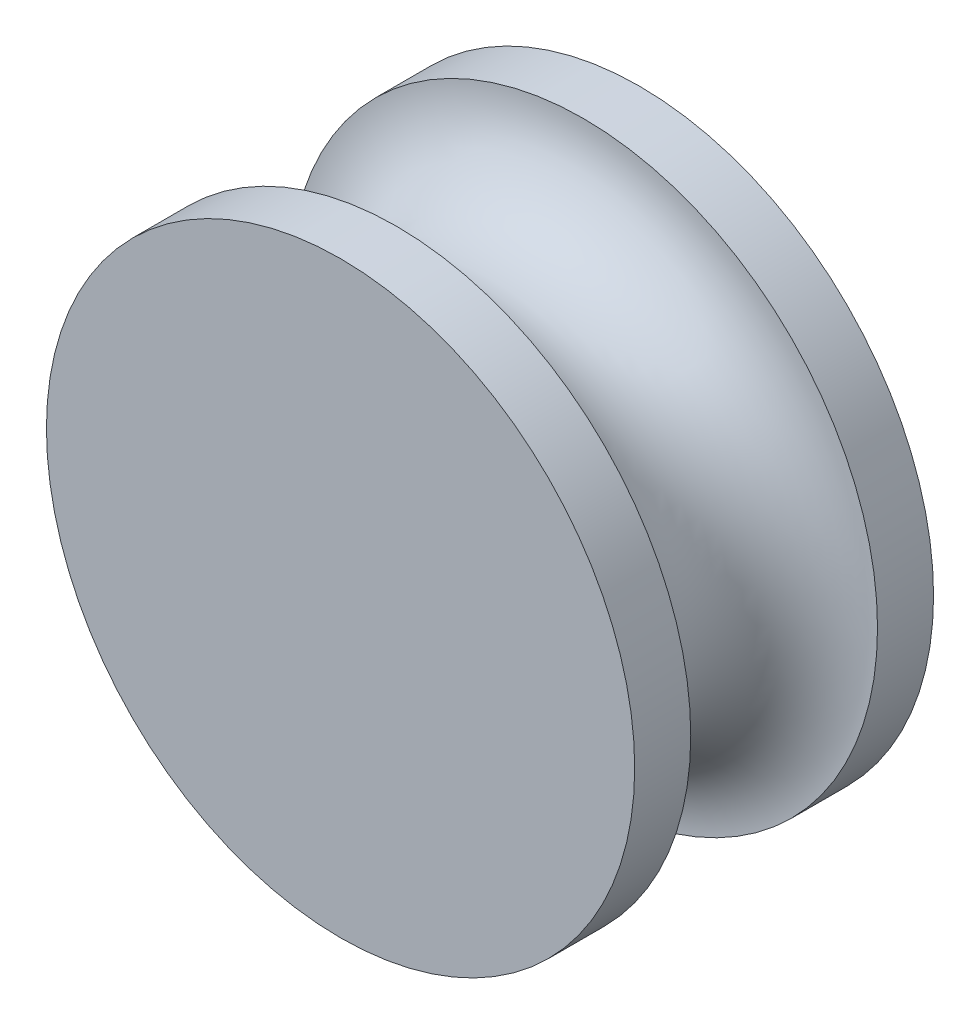
SolidWorks part; units mm, degrees
ref_plane "Front Plane" through (0, 0, 0) normal (0, 0, 1) x (1, 0, 0)
ref_plane "Top Plane" through (0, 0, 0) normal (0, 1, 0) x (1, 0, 0)
ref_plane "Right Plane" through (0, 0, 0) normal (1, 0, 0) x (0, 0, -1)
sketch "Sketch1" plane through (0, 0, 0) normal (0, 0, 1) x (1, 0, 0)
  circle A0 centre (0, 0) radius 25
  dimension "D1" = 50
extrude "Boss-Extrude1" add sketch "Sketch1" along normal mid plane 25.4
sketch "Sketch2" plane through (0, 0, 0) normal (0, 1, 0) x (1, 0, 0)
  line L1 (-25, 12.7) -> (-25, -12.7) construction
  line L2 (-25, 12.7) -> (-25, 7.9375) construction
  line L3 (-25, -7.9375) -> (-25, -12.7) construction
  line L4 (-25, 7.9375) -> (-25, -7.9375)
  arc A1 (-25, 7.9375) -> (-25, -7.9375) centre (-25, 0) cw
  point P7 (-20.8663, -11.1496)
  point P8 (0, 0)
  point P9 (-20.8663, -10.7315)
  point P10 (-25, 0)
  dimension "D1" = 7.9375
ref_axis "Axis1" through (0, 0, 12.7) along (0, 0, -1)
revolve "Cut-Revolve1" cut sketch "Sketch2" angle 360 about axis through (0, 0, 12.7) along (0, 0, -1)
